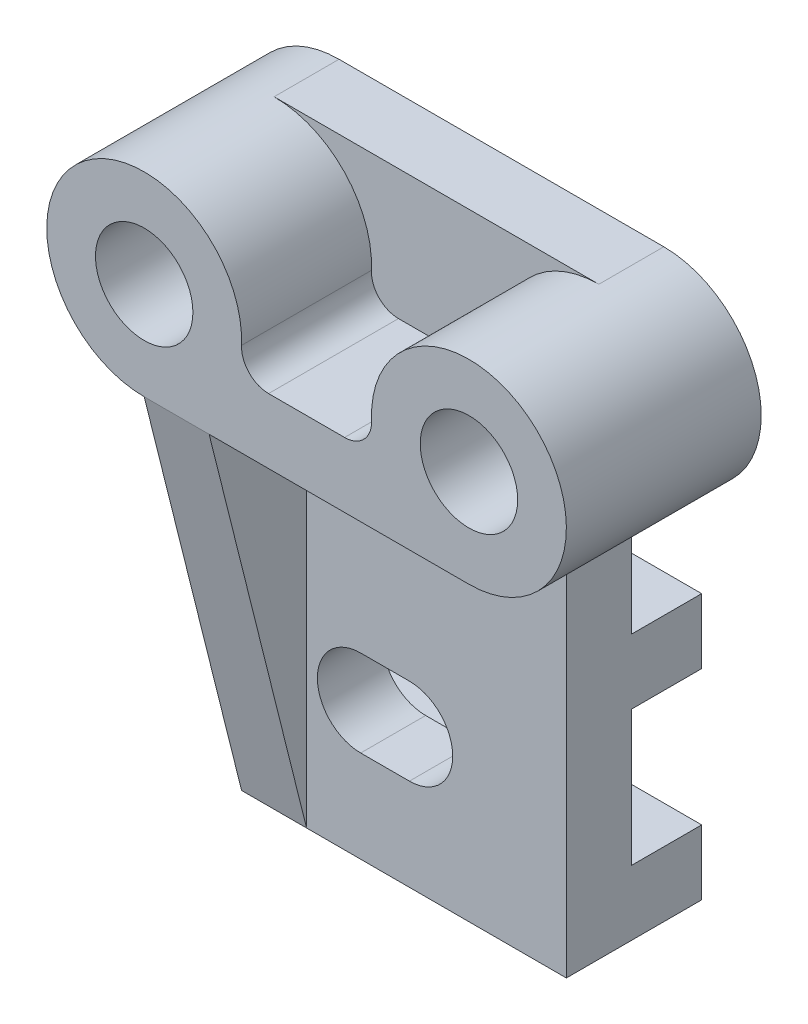
SolidWorks part; units mm, degrees
ref_plane "Front Plane" through (0, 0, 0) normal (0, 0, 1) x (1, 0, 0)
ref_plane "Top Plane" through (0, 0, 0) normal (0, 1, 0) x (1, 0, 0)
ref_plane "Right Plane" through (0, 0, 0) normal (1, 0, 0) x (0, 0, -1)
sketch "Sketch1" plane through (0, 0, 0) normal (0, 0, 1) x (1, 0, 0)
  line L0 (0, -18) -> (60, -18)
  line L2 (22.9783, -6) -> (37.0217, -6)
  circle A0 centre (0, 0) radius 9
  arc A1 (17.983, -0.7826) -> (0, -18) centre (0, 0) ccw
  circle A2 centre (60, 0) radius 9
  arc A3 (60, -18) -> (42.017, -0.7826) centre (60, 0) ccw
  arc A4 (42.017, -0.7826) -> (37.0217, -6) centre (37.0217, -1) cw
  arc A5 (22.9783, -6) -> (17.983, -0.7826) centre (22.9783, -1) cw
  dimension "D1" = 18
  dimension "D4" = 12
  dimension "D5" = 5
  dimension "D3" = 60
extrude "Boss-Extrude1" add sketch "Sketch1" along normal blind 36
sketch "Sketch2" plane through (0, 0, 0) normal (0, 0, -1) x (-1, 0, 0)
  line L0 (-60, 18) -> (0, 18)
  line L1 (-37.0217, -6) -> (-22.9783, -6)
  arc A0 (-42.017, -0.7826) -> (-60, -18) centre (-60, 0) ccw construction
  arc A1 (0, -18) -> (-17.983, -0.7826) centre (0, 0) ccw construction
  arc A2 (-42.017, -0.7826) -> (-60, 18) centre (-60, 0) ccw
  arc A3 (0, 18) -> (-17.983, -0.7826) centre (0, 0) ccw
  arc A4 (-37.0217, -6) -> (-42.017, -0.7826) centre (-37.0217, -1) cw
  arc A5 (-22.9783, -6) -> (-17.983, -0.7826) centre (-22.9783, -1) ccw
  dimension "D1" = 60
extrude "Boss-Extrude2" add sketch "Sketch2" against normal blind 12
ref_plane "Plane1" through (0, 0, 6) normal (0, 0, -1) x (-1, 0, 0)
sketch "Sketch3" plane through (0, 0, 6) normal (0, 0, -1) x (-1, 0, 0)
  line L0 (-60, -18) -> (-60, -90)
  line L1 (-60, -90) -> (0, -90)
  line L2 (0, -90) -> (0, -18)
  line L3 (-60, -18) -> (0, -18)
  line L4 (-31, -65) -> (-22, -65) construction
  line L5 (-31, -57) -> (-22, -57)
  line L6 (-31, -73) -> (-22, -73)
  arc A0 (-31, -57) -> (-31, -73) centre (-31, -65) ccw
  arc A1 (-22, -73) -> (-22, -57) centre (-22, -65) ccw
  point P10 (-26.5, -65)
  dimension "D1" = 72
  dimension "D2" = 16
  dimension "D3" = 9
  dimension "D4" = 22
  dimension "D5" = 25
extrude "Boss-Extrude3" add sketch "Sketch3" against normal blind 12
sketch "Sketch4" plane through (60, 0, 0) normal (1, 0, 0) x (0, 0, -1)
  line L0 (-6, -41) -> (7, -41)
  line L1 (-6, -90) -> (7, -90)
  line L2 (-6, -90) -> (-6, -78)
  line L3 (-6, -78) -> (7, -78)
  line L4 (7, -90) -> (7, -78)
  line L5 (-6, -53) -> (7, -53)
  line L6 (7, -53) -> (7, -41)
  line L7 (-6, -53) -> (-6, -41)
  dimension "D1" = 13
  dimension "D2" = 12
  dimension "D3" = 25
  dimension "D4" = 13
  dimension "D5" = 12
extrude "Boss-Extrude4" add sketch "Sketch4" against normal blind 60
sketch "Sketch5" plane through (0, 0, 0) normal (-1, 0, 0) x (0, 0, 1)
  line L0 (18, -90) -> (36, -18)
  line L1 (36, -18) -> (18, -18)
  line L2 (36, -18) -> (18, -18) construction
  line L3 (18, -90) -> (18, -18) construction
  line L4 (18, -18) -> (18, -90)
extrude "Boss-Extrude5" add sketch "Sketch5" against normal blind 12
